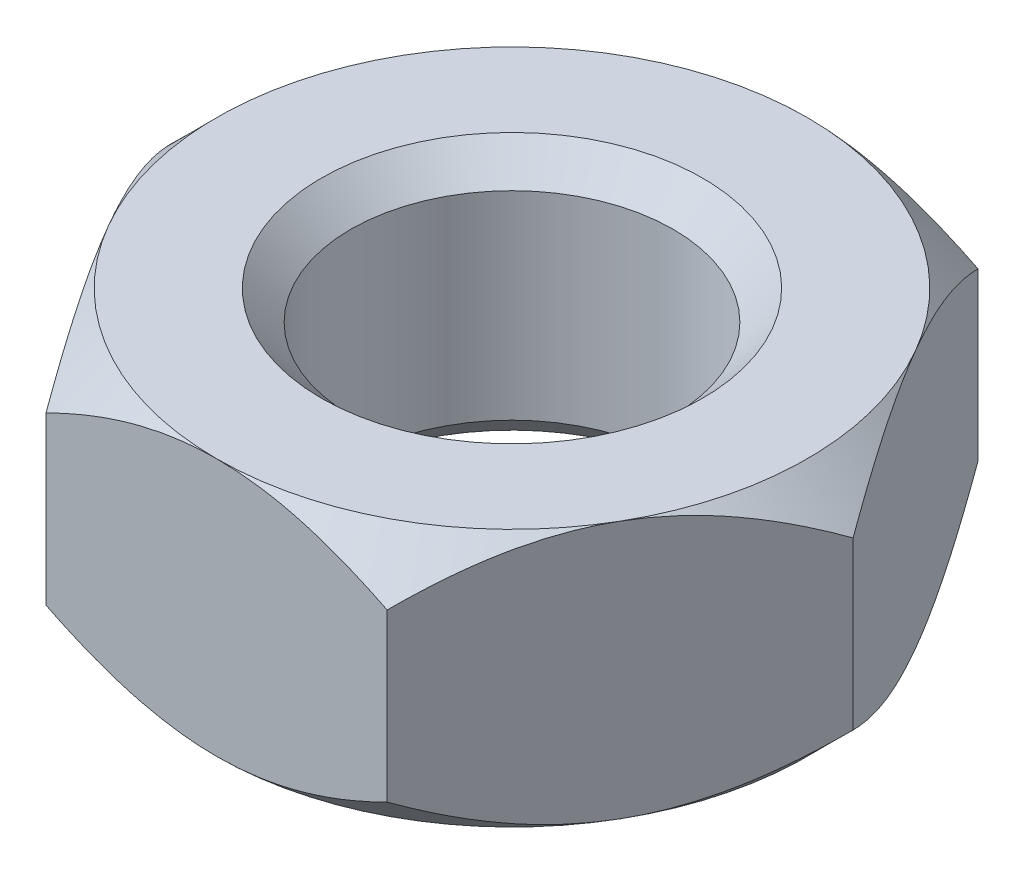
SolidWorks part; units mm, degrees
material "Cast Stainless Steel"
ref_plane "Front Plane" through (0, 0, 0) normal (0, 0, 1) x (1, 0, 0)
ref_plane "Top Plane" through (0, 0, 0) normal (0, 1, 0) x (1, 0, 0)
ref_plane "Right Plane" through (0, 0, 0) normal (1, 0, 0) x (0, 0, -1)
sketch "Sketch1" plane through (0, 0, 0) normal (0, 1, 0) x (1, 0, 0)
  line L0 (-3.1754, 0) -> (3.1754, 0) construction
  line L1 (3.1754, 0) -> (1.5877, 2.75)
  line L2 (1.5877, 2.75) -> (-1.5877, 2.75)
  line L3 (-1.5877, 2.75) -> (-3.1754, 0)
  line L4 (-3.1754, 0) -> (-1.5877, -2.75)
  line L5 (-1.5877, -2.75) -> (1.5877, -2.75)
  line L6 (1.5877, -2.75) -> (3.1754, 0)
  circle A0 centre (0, 0) radius 2.75 construction
  circle A1 centre (0, 0) radius 1.5
  point P12 (0, 0)
  dimension "D1" = 3
  dimension "D2" = 5.5
extrude "Boss-Extrude1" add sketch "Sketch1" along normal blind 2.4
sketch "Sketch3" plane through (0, 0, 0) normal (1, 0, 0) x (0, 0, -1)
  line L0 (-2.75, 0) -> (-3.45, 0.7)
  line L1 (-3.45, 0.7) -> (-3.45, 0)
  line L2 (-3.45, 0) -> (-2.75, 0)
  line L4 (-2.75, 1.2) -> (2.75, 1.2) construction
  line L6 (2.75, 2.4) -> (2.75, 0) construction
  line L7 (-3.45, 2.4) -> (-2.75, 2.4)
  line L8 (-3.45, 1.7) -> (-3.45, 2.4)
  line L9 (-2.75, 2.4) -> (-3.45, 1.7)
  line L10 (0, 0) -> (0, 2.4) construction
  line L12 (-2.75, 2.4) -> (-2.75, 0) construction
  point P7 (0, 1.2)
  dimension "D1" = 1.2
  dimension "D2" = 45
  dimension "D3" = 0.7
revolve "Cut-Revolve1" cut sketch "Sketch3" angle 360 about L10
chamfer "Chamfer1" distance 0.275 angle 45 2 edges at (0, 0, 1.5) (0, 2.4, 1.5)
equation "\"d\"= 3"
equation "\"m\"= 2.4"
equation "\"s\"= 5.5"
equation "\"e\"= 6.01"
equation "\"D1@Sketch1\"=\"d\""
equation "\"D2@Sketch1\"=\"s\""
equation "\"D1@Boss-Extrude1\"=\"m\""
equation "\"D1@Sketch3\"=\"m\"/2"
equation "\"D3@Sketch3\"=\"D1@Sketch3\"-0.5"
equation "\"D1@Chamfer1\"=\"s\"/20"
